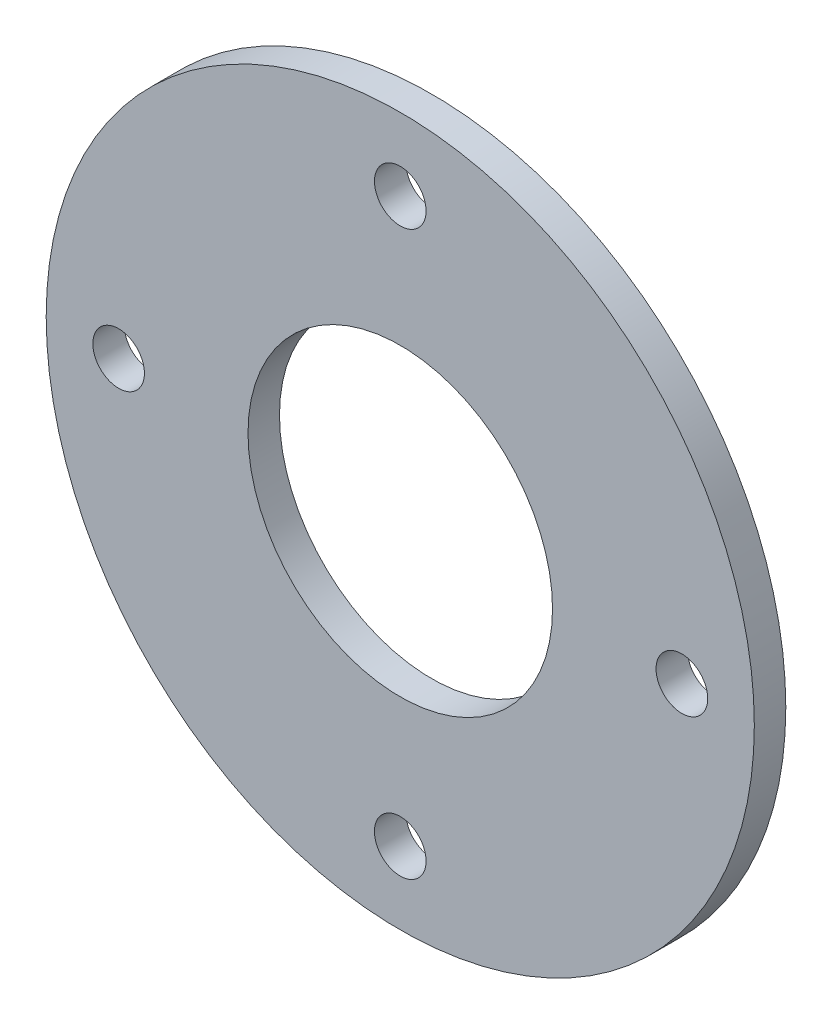
SolidWorks part; units mm, degrees
material "AISI 1020"
ref_plane "Front Plane" through (0, 0, 0) normal (0, 0, 1) x (1, 0, 0)
ref_plane "Top Plane" through (0, 0, 0) normal (0, 1, 0) x (1, 0, 0)
ref_plane "Right Plane" through (0, 0, 0) normal (1, 0, 0) x (0, 0, -1)
other "Configuration Table"
sketch "Sketch1" plane through (0, 0, 0) normal (0, 0, 1) x (1, 0, 0)
  circle A4 centre (0, 0) radius 114.3 construction
  circle A5 centre (0, 0) radius 49.15 construction
  circle A10 centre (0, 0) radius 114.3
  circle A11 centre (0, 0) radius 49.15
extrude "Extrude1" add sketch "Sketch1" along normal blind 10.16
hole_wizard "5/8 Clearance Hole1" positions "Sketch2" profile "Sketch3" hole size "5/8" standard "Ansi Inch" end condition through all
sketch "Sketch2" plane through (-61.2299, -86.9453, 0) normal (0, 0, -1) x (-1, 0, 0)
  line L0 (-61.2299, 86.9453) -> (160.2598, 86.9453) construction
  line L1 (-61.2299, 86.9453) -> (-61.2299, 296.6144) construction
  line L2 (-61.2299, 86.9453) -> (-291.9631, 86.9453) construction
  line L3 (-61.2299, 86.9453) -> (-61.2299, -121.1078) construction
  circle A0 centre (-61.2299, 86.9453) radius 90.9114 construction
  point P0 (-61.2299, 177.798)
  point P1 (29.6815, 86.9453)
  point P2 (-61.2299, -3.9661)
  point P3 (-152.1413, 86.9453)
sketch "Sketch3" plane through (0, 90.8528, 0) normal (1, 0, 0) x (0, 1, 0)
  line L0 (0, 0) -> (0, 10.16)
  line L1 (0, 10.16) -> (8.3337, 10.16)
  line L2 (8.3337, 10.16) -> (8.3337, 0)
  line L5 (8.3337, 0) -> (0, 0)
  line L11 (0, -6.35) -> (0, 107.95) construction
  dimension "Thru Hole Dia." = 16.6675
  dimension "Thru Hole Depth" = 10.16
